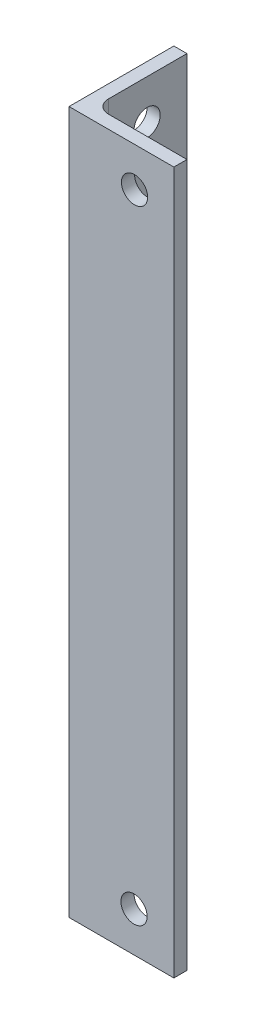
SolidWorks part; units mm, degrees
ref_plane "Front" through (0, 0, 0) normal (0, 0, 1) x (1, 0, 0)
ref_plane "Top" through (0, 0, 0) normal (0, 1, 0) x (1, 0, 0)
ref_plane "Right" through (0, 0, 0) normal (1, 0, 0) x (0, 0, -1)
sketch "Sketch1" plane through (0, 0, 0) normal (0, 1, 0) x (1, 0, 0)
  line L0 (0, 0) -> (3.175, 0)
  line L1 (3.175, 0) -> (3.175, -22.225)
  line L2 (3.175, -22.225) -> (25.4, -22.225)
  line L3 (25.4, -22.225) -> (25.4, -25.4)
  line L4 (25.4, -25.4) -> (0, -25.4)
  line L5 (0, -25.4) -> (0, 0)
  dimension "D1" = 25.4
  dimension "D2" = 25.4
  dimension "D3" = 3.175
  dimension "D4" = 3.175
extrude "Boss-Extrude1" add sketch "Sketch1" along normal blind 170.18
fillet "Fillet1" radius 3.175 1 edges at (3.175, 85.09, 22.225)
sketch "Sketch2" plane through (0, 0, 0) normal (-1, 0, 0) x (0, 0, 1)
  line L1 (0, 170.18) -> (0, 0) construction
  line L2 (0, 170.18) -> (25.4, 170.18) construction
  circle A0 centre (9.652, 160.528) radius 3.175
  dimension "D1" = 6.35
  dimension "D2" = 9.652
  dimension "D3" = 9.652
extrude "Cut-Extrude1" cut sketch "Sketch2" against normal through all
sketch "Sketch3" plane through (0, 0, 0) normal (-1, 0, 0) x (0, 0, 1)
  line L0 (0, 170.18) -> (0, 0) construction
  line L1 (0, 0) -> (25.4, 0) construction
  circle A0 centre (9.652, 9.652) radius 3.175
  dimension "D1" = 6.35
  dimension "D2" = 9.652
  dimension "D3" = 9.652
extrude "Cut-Extrude2" cut sketch "Sketch3" against normal through all
sketch "Sketch4" plane through (0, 0, 22.225) normal (0, 0, -1) x (-1, 0, 0)
  line L0 (-25.4, 170.18) -> (-25.4, 0) construction
  line L1 (-25.4, 0) -> (-6.35, 0) construction
  circle A0 centre (-15.748, 9.652) radius 3.175
  dimension "D1" = 6.35
  dimension "D2" = 9.652
  dimension "D3" = 9.652
extrude "Cut-Extrude3" cut sketch "Sketch4" against normal through all
sketch "Sketch5" plane through (0, 0, 22.225) normal (0, 0, -1) x (-1, 0, 0)
  line L0 (-25.4, 170.18) -> (-25.4, 0) construction
  line L1 (-25.4, 170.18) -> (-6.35, 170.18) construction
  circle A0 centre (-15.875, 160.655) radius 3.175
  dimension "D1" = 6.35
  dimension "D2" = 9.525
  dimension "D3" = 9.525
extrude "Cut-Extrude4" cut sketch "Sketch5" against normal through all
